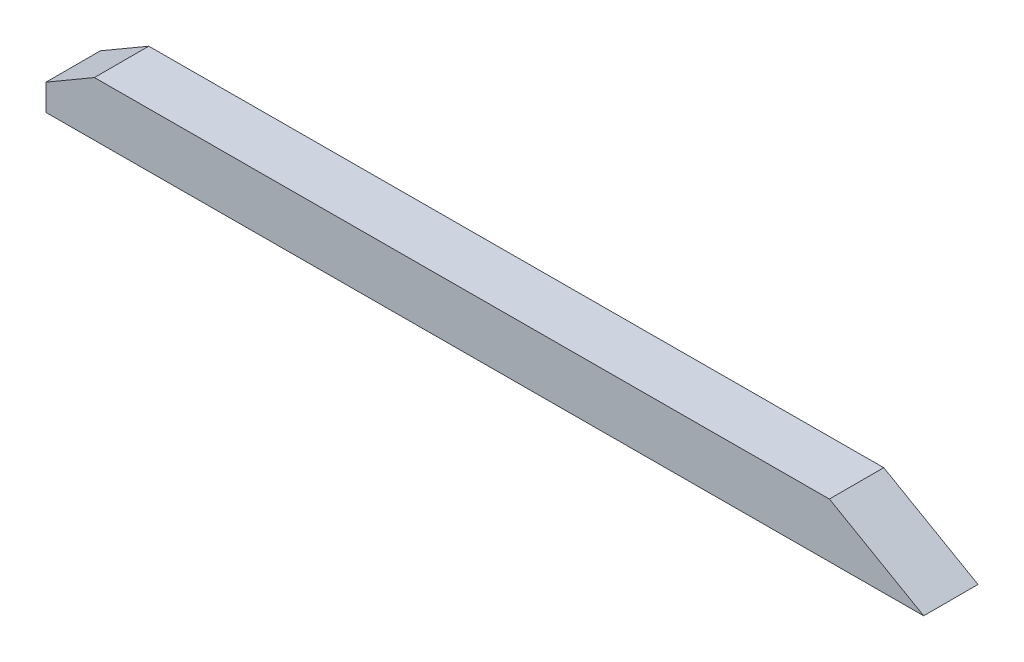
SolidWorks part; units mm, degrees
ref_plane "Front Plane" through (0, 0, 0) normal (0, 0, 1) x (1, 0, 0)
ref_plane "Top Plane" through (0, 0, 0) normal (0, 1, 0) x (1, 0, 0)
ref_plane "Right Plane" through (0, 0, 0) normal (1, 0, 0) x (0, 0, -1)
sketch "Sketch1" plane through (0, 0, 0) normal (0, 0, 1) x (1, 0, 0)
  line L0 (-345.2816, 30.6971) -> (-74.6616, 31.6053)
  line L1 (-363.1137, 10.6372) -> (-39.9537, 11.7216)
  line L2 (-74.6616, 31.6053) -> (-39.9537, 11.7216)
  line L3 (-363.1137, 20.3072) -> (-345.2816, 30.6971)
  line L5 (-363.1137, 10.6372) -> (-363.1137, 20.3072)
  point P6 (-345.2564, 30.6971)
  point P7 (-363.1137, 20.3072)
  dimension "D1" = 20
  dimension "D2" = 323.16
  dimension "D3" = 26.84
  dimension "D4" = 270.62
  dimension "D5" = 9.67
  dimension "D6" = 20.66
extrude "Boss-Extrude1" add sketch "Sketch1" along normal blind 20
